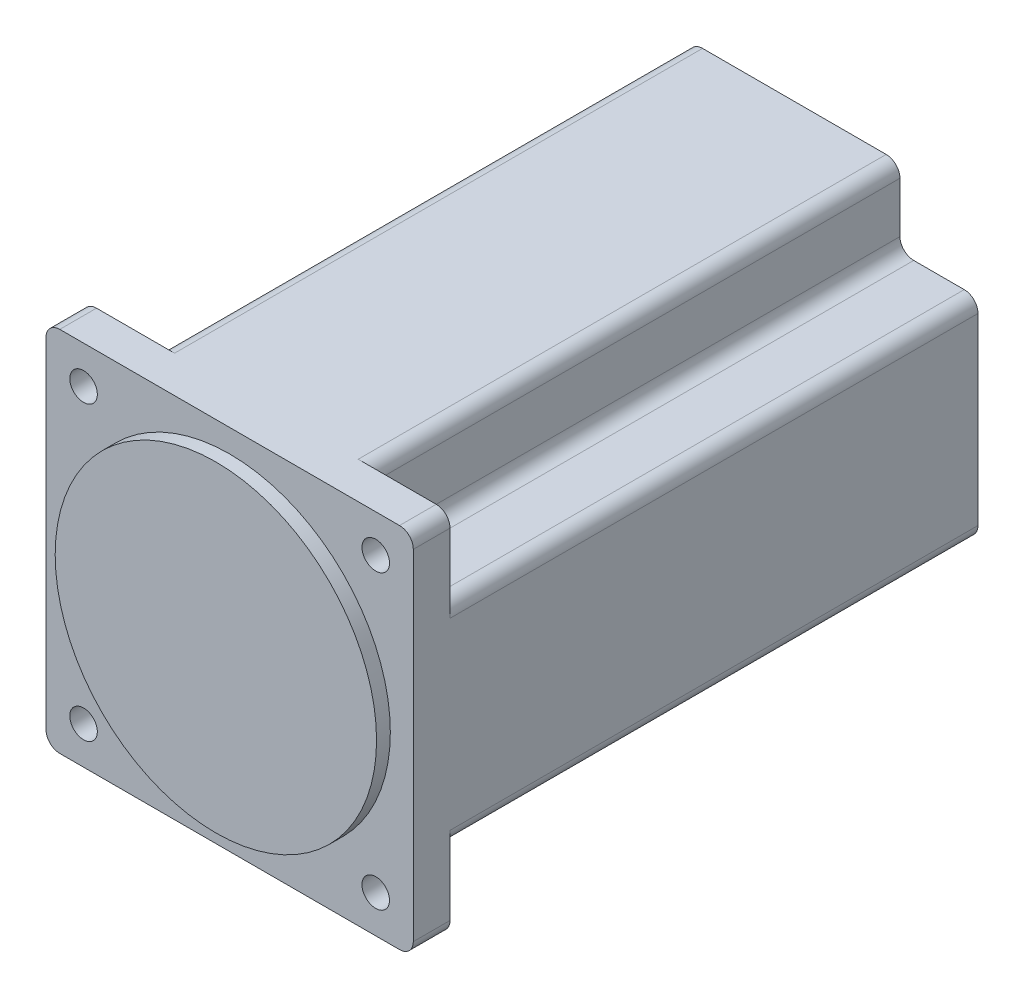
SolidWorks part; units mm, degrees
material "Titanium Ti-8Mn, Annealed"
ref_plane "Front" through (0, 0, 0) normal (0, 0, 1) x (1, 0, 0)
ref_plane "Top" through (0, 0, 0) normal (0, 1, 0) x (1, 0, 0)
ref_plane "Right" through (0, 0, 0) normal (1, 0, 0) x (0, 0, -1)
sketch "Sketch1" plane through (0, 0, 0) normal (0, 0, 1) x (1, 0, 0)
  line L1 (-40, 40) -> (40, 40)
  line L2 (-40, 40) -> (-40, -40)
  line L3 (-40, -40) -> (40, -40)
  line L4 (40, 40) -> (40, -40)
  line L5 (-40, 40) -> (40, -40) construction
  line L6 (-40, -40) -> (40, 40) construction
  circle A0 centre (-31.8198, 31.8198) radius 3
  circle A1 centre (31.8198, 31.8198) radius 3
  circle A2 centre (31.8198, -31.8198) radius 3
  circle A3 centre (-31.8198, -31.8198) radius 3
  point P0 (0, 0)
  point P11 (0, 0)
  point P14 (0, 0)
  point P17 (0, 0)
  point P20 (0, 0)
  dimension "D3" = 6
  dimension "D1" = 80
  dimension "D2" = 80
  dimension "D4" = 45
  dimension "D5" = 4
extrude "Boss-Extrude1" add sketch "Sketch1" along normal blind 123
sketch "Sketch2" plane through (0, 0, 123) normal (0, 0, 1) x (1, 0, 0)
  circle A0 centre (0, 0) radius 35
  dimension "D1" = 70
extrude "Boss-Extrude2" add sketch "Sketch2" along normal blind 3
sketch "Sketch4" plane through (0, 0, 0) normal (0, 0, -1) x (-1, 0, 0)
  line L0 (23, 40) -> (23, 23)
  line L1 (-40, 40) -> (-23, 40)
  line L2 (-40, 40) -> (-40, 23)
  line L3 (-40, 23) -> (-23, 23)
  line L4 (-23, 40) -> (-23, 23)
  line L5 (40, 23) -> (23, 23)
  line L6 (40, 40) -> (23, 40)
  line L7 (40, 40) -> (40, 23)
  line L8 (40, -23) -> (23, -23)
  line L9 (23, -40) -> (23, -23)
  line L10 (40, -40) -> (40, -23)
  line L11 (40, -40) -> (23, -40)
  line L12 (-23, -40) -> (-23, -23)
  line L13 (-40, -23) -> (-23, -23)
  line L14 (-40, -40) -> (-23, -40)
  line L15 (-40, -40) -> (-40, -23)
  point P20 (0, 0)
  dimension "D2" = 17
  dimension "D1" = 17
  dimension "D3" = 4
extrude "Cut-Extrude1" cut sketch "Sketch4" against normal blind 115
fillet "Fillet1" radius 3 16 edges at (40, 23, 57.5) (23, 23, 57.5) (-23, 40, 57.5) (-23, 23, 57.5) (-40, 23, 57.5) (-40, -23, 57.5) (-23, -23, 57.5) (-23, -40, 57.5) (23, -40, 57.5) (23, -23, 57.5) (40, -23, 57.5) (23, 40, 57.5) (-40, 40, 119) (-40, -40, 119) (40, -40, 119) (40, 40, 119)
